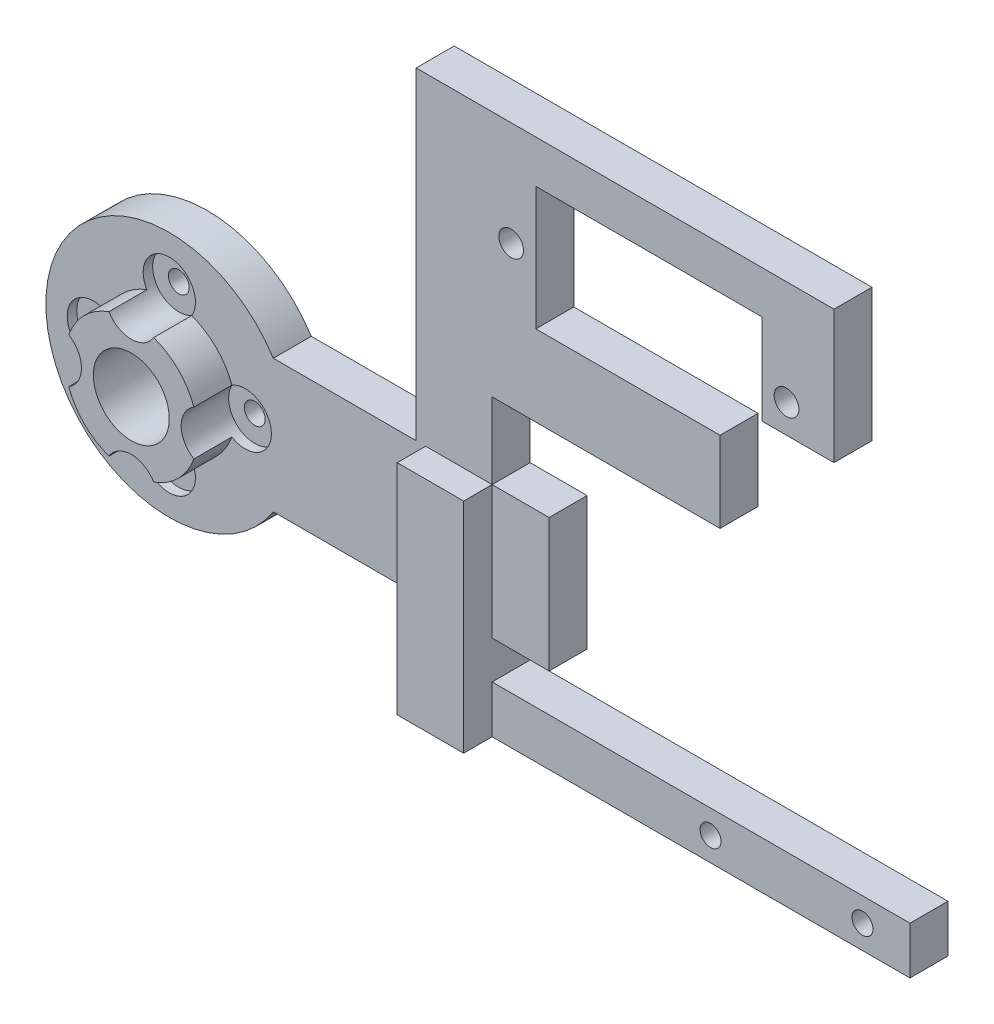
SolidWorks part; units mm, degrees
ref_plane "Front Plane" through (0, 0, 0) normal (0, 0, 1) x (1, 0, 0)
ref_plane "Top Plane" through (0, 0, 0) normal (0, 1, 0) x (1, 0, 0)
ref_plane "Right Plane" through (0, 0, 0) normal (1, 0, 0) x (0, 0, -1)
sketch "Elbow_horn_flange_profile" plane through (0, 0, 0) normal (0, 0, 1) x (1, 0, 0)
  circle A0 centre (0, 0) radius 13
  dimension "D1" = 26
extrude "Elbow_horn_flange" add sketch "Elbow_horn_flange_profile" along normal blind 4
sketch "Forearm_web_profile" plane through (0, 0, 0) normal (0, 0, 1) x (1, 0, 0)
  line L1 (0, -7) -> (40, -7)
  line L2 (0, -7) -> (0, 7)
  line L3 (0, 7) -> (40, 7)
  line L4 (40, -7) -> (40, 7)
  dimension "D1" = 40
  dimension "D2" = 14
extrude "Forearm_web" add sketch "Forearm_web_profile" along normal blind 4
sketch "Gripper_mount_rib_profile" plane through (0, 0, 0) normal (0, 0, 1) x (1, 0, 0)
  line L1 (26, 0) -> (34, 0)
  line L2 (26, 0) -> (26, 30)
  line L3 (26, 30) -> (34, 30)
  line L4 (34, 0) -> (34, 30)
  dimension "D1" = 8
  dimension "D2" = 30
extrude "Gripper_mount_rib" add sketch "Gripper_mount_rib_profile" along normal blind 4
sketch "Gripper_servo_mount_profile" plane through (0, 0, 0) normal (0, 0, 1) x (1, 0, 0)
  line L1 (26, 15) -> (70, 15)
  line L2 (26, 15) -> (26, 41)
  line L3 (26, 41) -> (70, 41)
  line L4 (70, 15) -> (70, 41)
  dimension "D1" = 44
  dimension "D2" = 26
extrude "Gripper_servo_mount" add sketch "Gripper_servo_mount_profile" along normal blind 4
sketch "Grip_SG90_body_clearance_profile" plane through (0, 0, 0) normal (0, 0, 1) x (1, 0, 0)
  line L1 (38.6, 23.5) -> (62.4, 23.5)
  line L2 (38.6, 23.5) -> (38.6, 36.5)
  line L3 (38.6, 36.5) -> (62.4, 36.5)
  line L4 (62.4, 23.5) -> (62.4, 36.5)
  dimension "D1" = 23.8
  dimension "D2" = 13
extrude "Grip_SG90_body_clearance" cut sketch "Grip_SG90_body_clearance_profile" along normal through all from offset 5
sketch "Moving_finger_sweep_relief_profile" plane through (0, 0, 0) normal (0, 0, 1) x (1, 0, 0)
  line L1 (58, 14) -> (71, 14)
  line L2 (58, 14) -> (58, 27)
  line L3 (58, 27) -> (71, 27)
  line L4 (71, 14) -> (71, 27)
  dimension "D1" = 13
  dimension "D2" = 13
extrude "Moving_finger_sweep_relief" cut sketch "Moving_finger_sweep_relief_profile" along normal through all from offset 5
sketch "Grip_servo_tab_fasteners_profile" plane through (0, 0, 0) normal (0, 0, 1) x (1, 0, 0)
  circle A0 centre (36, 30) radius 1.3
  circle A1 centre (65, 30) radius 1.3
  dimension "D1" = 2.6
  dimension "D2" = 2.6
extrude "Grip_servo_tab_fasteners" cut sketch "Grip_servo_tab_fasteners_profile" along normal through all from offset 50
sketch "Fixed_finger_spine_profile" plane through (0, 0, 0) normal (0, 0, 1) x (1, 0, 0)
  line L1 (30, -16) -> (78, -16)
  line L2 (30, -16) -> (30, -11)
  line L3 (30, -11) -> (78, -11)
  line L4 (78, -16) -> (78, -11)
  dimension "D1" = 48
  dimension "D2" = 5
extrude "Fixed_finger_spine" add sketch "Fixed_finger_spine_profile" along normal blind 4
sketch "Fixed_finger_root_profile" plane through (0, 0, 0) normal (0, 0, 1) x (1, 0, 0)
  line L1 (27, -16) -> (34, -16)
  line L2 (27, -16) -> (27, 7)
  line L3 (27, 7) -> (34, 7)
  line L4 (34, -16) -> (34, 7)
  dimension "D1" = 7
  dimension "D2" = 23
extrude "Fixed_finger_root" add sketch "Fixed_finger_root_profile" along normal blind 7
sketch "Elbow_center_screw_access_profile" plane through (0, 0, 0) normal (0, 0, 1) x (1, 0, 0)
  circle A0 centre (0, 0) radius 4
  dimension "D1" = 8
extrude "Elbow_center_screw_access" cut sketch "Elbow_center_screw_access_profile" along normal through all from offset 50
sketch "Elbow_dowel_support_hub_profile" plane through (0, 0, 0) normal (0, 0, 1) x (1, 0, 0)
  circle A0 centre (0, 0) radius 7
  circle A1 centre (0, 0) radius 4
  dimension "D1" = 14
  dimension "D2" = 8
extrude "Elbow_dowel_support_hub" add sketch "Elbow_dowel_support_hub_profile" along normal blind 4 from offset 4
sketch "Elbow_horn_fasteners_profile" plane through (0, 0, 0) normal (0, 0, 1) x (1, 0, 0)
  circle A0 centre (0, -8) radius 1.1
  circle A1 centre (0, 8) radius 1.1
  circle A2 centre (-8, 0) radius 1.1
  circle A3 centre (8, 0) radius 1.1
  dimension "D1" = 2.2
  dimension "D2" = 2.2
  dimension "D3" = 2.2
  dimension "D4" = 2.2
extrude "Elbow_horn_fasteners" cut sketch "Elbow_horn_fasteners_profile" along normal through all from offset 50
sketch "Elbow_horn_washer_recess_profile" plane through (0, 0, 0) normal (0, 0, 1) x (1, 0, 0)
  circle A0 centre (0, -8) radius 2.75
  circle A1 centre (0, 8) radius 2.75
  circle A2 centre (-8, 0) radius 2.75
  circle A3 centre (8, 0) radius 2.75
  dimension "D1" = 5.5
  dimension "D2" = 5.5
  dimension "D3" = 5.5
  dimension "D4" = 5.5
extrude "M2x8_washer_and_hub_clearance" cut sketch "Elbow_horn_washer_recess_profile" along normal blind 5 from offset 3
sketch "Fixed_pad_keeper_fasteners_profile" plane through (0, 0, 0) normal (0, 0, 1) x (1, 0, 0)
  circle A0 centre (57, -13.5) radius 1.1
  circle A1 centre (73, -13.5) radius 1.1
  dimension "D1" = 2.2
  dimension "D2" = 2.2
extrude "Fixed_pad_keeper_fasteners" cut sketch "Fixed_pad_keeper_fasteners_profile" along normal through all from offset 50
